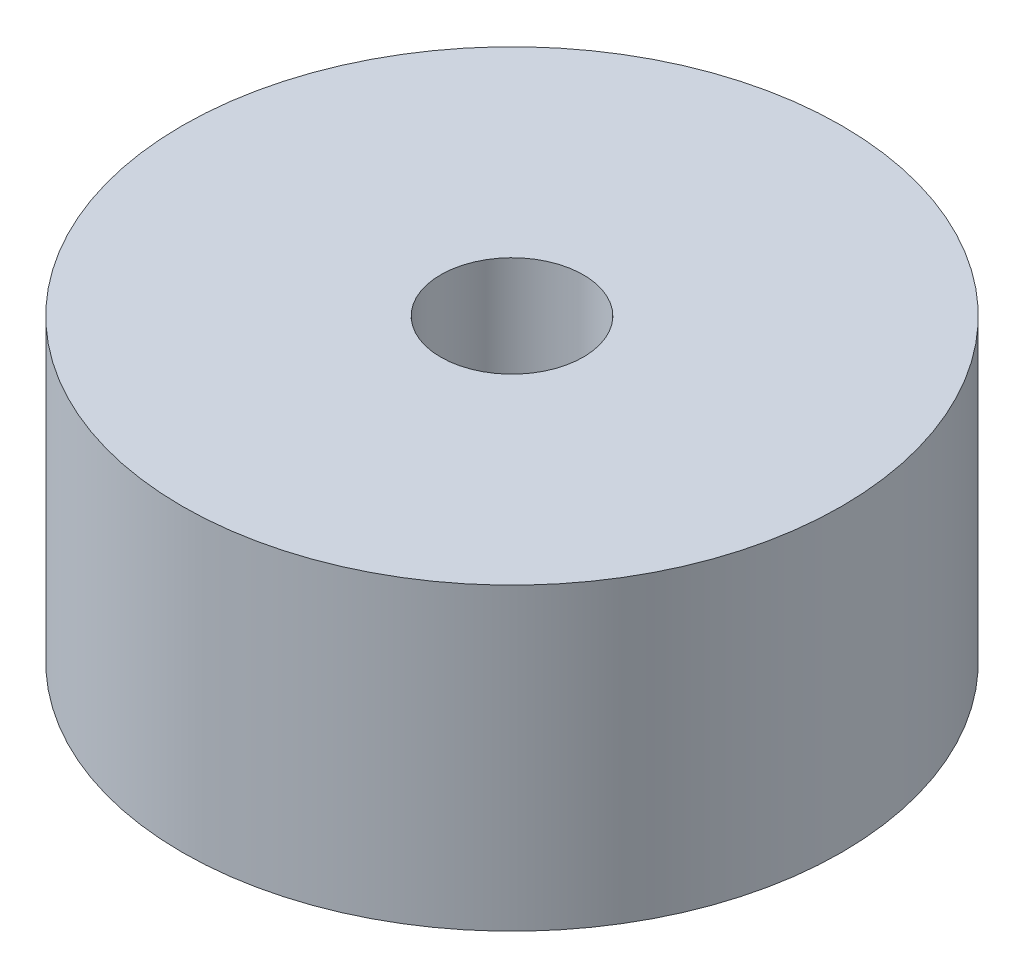
SolidWorks part; units mm, degrees
ref_plane "Front Plane" through (0, 0, 0) normal (0, 0, 1) x (1, 0, 0)
ref_plane "Top Plane" through (0, 0, 0) normal (0, 1, 0) x (1, 0, 0)
ref_plane "Right Plane" through (0, 0, 0) normal (1, 0, 0) x (0, 0, -1)
sketch "Sketch1" plane through (0, 0, 0) normal (0, 1, 0) x (1, 0, 0)
  line L0 (0, 0) -> (99.948, 0) construction
  circle A1 centre (0, 0) radius 1.19
  circle A2 centre (0, 0) radius 5.5
  dimension "D1" = 2.38
  dimension "D2" = 11
extrude "Boss-Extrude1" add sketch "Sketch1" along normal blind 5
